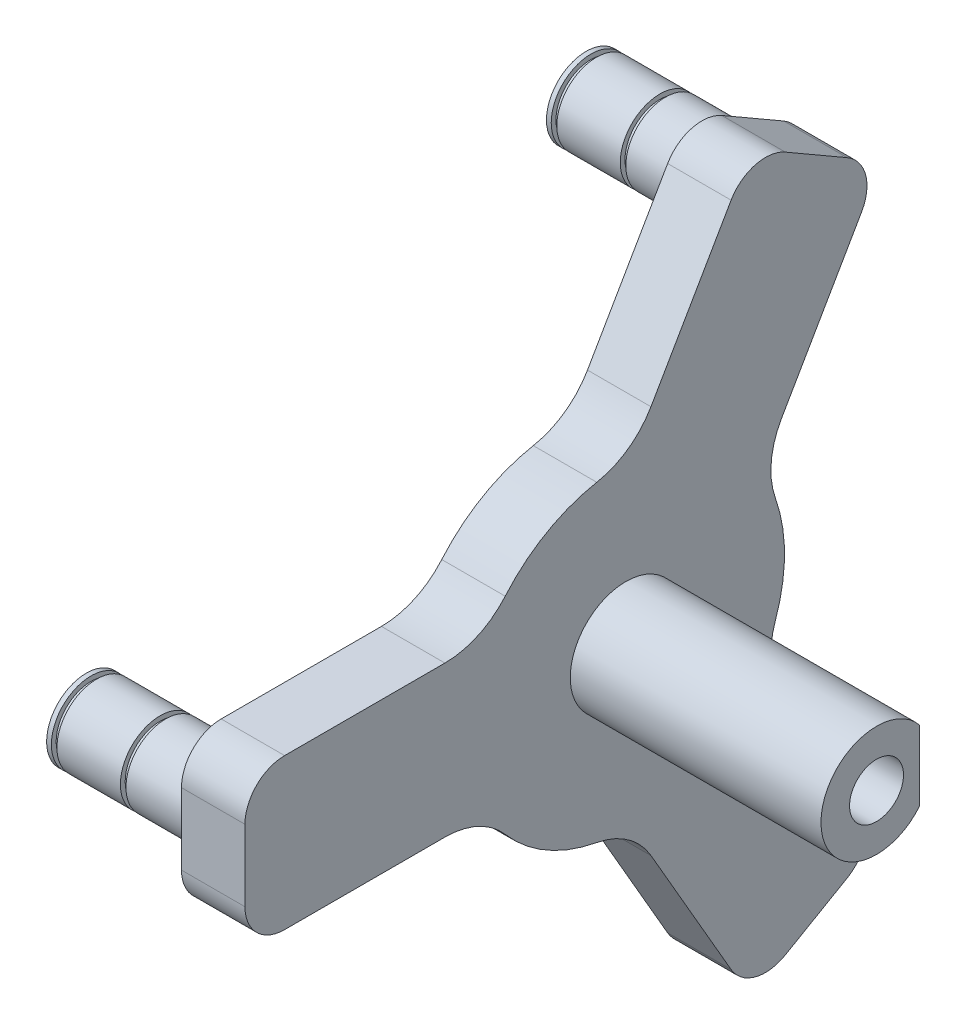
SolidWorks part; units mm, degrees
ref_plane "Front Plane" through (0, 0, 0) normal (1, 0, 0) x (0, 1, 0)
ref_plane "Top Plane" through (0, 0, 0) normal (0, 0, 1) x (0, 1, 0)
ref_plane "Right Plane" through (0, 0, 0) normal (0, 1, 0) x (-1, 0, 0)
sketch "Sketch1" plane through (0, 0, 0) normal (1, 0, 0) x (0, 1, 0)
  line L0 (0, 0) -> (0, 48) construction
  line L1 (46.3192, -15.7728) -> (19.9918, -0.5726) construction
  line L2 (36.8192, -32.2272) -> (10.4918, -17.0271) construction
  line L3 (-9.5, 48) -> (9.5, 48) construction
  line L4 (9.5, 48) -> (9.5, 17.5997) construction
  line L5 (-9.5, 48) -> (-9.5, 17.5997) construction
  line L6 (46.3192, -15.7728) -> (36.8192, -32.2272) construction
  line L7 (-36.8192, -32.2272) -> (-10.4918, -17.0271) construction
  line L8 (-46.3192, -15.7728) -> (-19.9918, -0.5726) construction
  line L9 (-36.8192, -32.2272) -> (-46.3192, -15.7728) construction
  line L10 (-19.9918, -0.5726) -> (-46.3192, -15.7728)
  line L11 (-46.3192, -15.7728) -> (-36.8192, -32.2272)
  line L12 (-36.8192, -32.2272) -> (-10.4918, -17.0271)
  line L13 (10.4918, -17.0271) -> (36.8192, -32.2272)
  line L14 (36.8192, -32.2272) -> (46.3192, -15.7728)
  line L15 (46.3192, -15.7728) -> (19.9918, -0.5726)
  line L16 (9.5, 17.5997) -> (9.5, 48)
  line L17 (9.5, 48) -> (-9.5, 48)
  line L18 (-9.5, 48) -> (-9.5, 17.5997)
  arc A0 (-9.5, 17.5997) -> (-19.9918, -0.5726) centre (0, 0) ccw construction
  arc A1 (19.9918, -0.5726) -> (9.5, 17.5997) centre (0, 0) ccw construction
  arc A2 (-10.4918, -17.0271) -> (10.4918, -17.0271) centre (0, 0) ccw construction
  arc A3 (-10.4918, -17.0271) -> (10.4918, -17.0271) centre (0, 0) ccw
  arc A4 (-10.4918, -17.0271) -> (10.4918, -17.0271) centre (0, 0) ccw construction
  arc A5 (-10.4918, -17.0271) -> (10.4918, -17.0271) centre (0, 0) ccw construction
  arc A6 (19.9918, -0.5726) -> (9.5, 17.5997) centre (0, 0) ccw construction
  arc A7 (19.9918, -0.5726) -> (9.5, 17.5997) centre (0, 0) ccw
  arc A8 (19.9918, -0.5726) -> (9.5, 17.5997) centre (0, 0) ccw construction
  arc A9 (-9.5, 17.5997) -> (-19.9918, -0.5726) centre (0, 0) ccw construction
  arc A10 (-9.5, 17.5997) -> (-19.9918, -0.5726) centre (0, 0) ccw construction
  arc A11 (-9.5, 17.5997) -> (-19.9918, -0.5726) centre (0, 0) ccw
  point P18 (0, 0)
  dimension "D4" = 40
  dimension "D1" = 19
  dimension "D2" = 3
  dimension "D3" = 48
extrude "Boss-Extrude2" add sketch "Sketch1" along normal blind 8
fillet "Fillet1" radius 10 6 edges at (4, 10.4918, -17.0271) (4, -10.4918, -17.0271) (4, -19.9918, -0.5726) (4, -9.5, 17.5997) (4, 19.9918, -0.5726) (4, 9.5, 17.5997)
fillet "Fillet3" radius 5 2 edges at (4, 9.5, 48) (4, -9.5, 48)
fillet "Fillet4" radius 5 4 edges at (4, 46.3192, -15.7728) (4, 36.8192, -32.2272) (4, -36.8192, -32.2272) (4, -46.3192, -15.7728)
sketch "Sketch2" plane through (0, 0, 0) normal (-1, 0, 0) x (0, -1, 0)
  line L0 (0, 0) -> (0, 42) construction
  line L1 (0, 0) -> (-36.3731, -21) construction
  line L2 (0, 0) -> (36.3731, -21) construction
  circle A0 centre (0, 42) radius 5
  circle A1 centre (-36.3731, -21) radius 5
  circle A2 centre (36.3731, -21) radius 5
  dimension "D1" = 10
  dimension "D2" = 42
sketch "Sketch3" plane through (0, 0, 0) normal (-1, 0, 0) x (0, -1, 0)
  circle A0 centre (0, 0) radius 5
  dimension "D1" = 10
extrude "Boss-Extrude3" add sketch "Sketch3" along normal blind 10
extrude "Boss-Extrude4" add sketch "Sketch2" along normal blind 18
sketch "Sketch4" plane through (8, 0, 0) normal (1, 0, 0) x (0, 1, 0)
  circle A0 centre (0, 0) radius 7
  dimension "12" = 14
extrude "Boss-Extrude5" add sketch "Sketch4" along normal blind 31.6
sketch "Sketch5" plane through (39.6, 0, 0) normal (1, 0, 0) x (0, 1, 0)
  line L0 (-4.45, -5.4035) -> (4.45, -5.4035)
  circle A0 centre (0, 0) radius 7 construction
  circle A1 centre (0, 0) radius 7 construction
  arc A2 (-4.45, -5.4035) -> (4.45, -5.4035) centre (0, 0) ccw
  dimension "D1" = 8.9
extrude "Cut-Extrude1" cut sketch "Sketch5" against normal blind 8
sketch "Sketch7" plane through (0, 0, 0) normal (0, 1, 0) x (-1, 0, 0)
  line L0 (18, 47) -> (0, 47) construction
  line L6 (8.7, 46.4) -> (8, 46.4)
  line L12 (8.7, 46.4) -> (8.7, 47.6)
  line L13 (8.7, 47.6) -> (8, 47.6)
  line L14 (21.8155, 42) -> (-10.848, 42) construction
  line L15 (8, 46.4) -> (8, 47.6)
  line L16 (8.7, 46.4) -> (8, 47.6) construction
  line L17 (8.7, 47.6) -> (8, 46.4) construction
  line L18 (17.4, 46.4) -> (16.7, 46.4)
  line L19 (17.4, 46.4) -> (17.4, 47.6)
  line L20 (17.4, 47.6) -> (16.7, 47.6)
  line L21 (16.7, 46.4) -> (16.7, 47.6)
  line L22 (17.4, 46.4) -> (16.7, 47.6) construction
  line L23 (17.4, 47.6) -> (16.7, 46.4) construction
  line L25 (0, 37) -> (0, 47) construction
  point P0 (8.35, 47)
  point P7 (17.05, 47)
  dimension "D1" = 0.7
  dimension "D2" = 0.6
  dimension "D3" = 8
  dimension "D4" = 5
  dimension "D5" = 8
revolve "Cut-Revolve1" cut sketch "Sketch7" angle 360 about L14
pattern_circular "CirPattern1" count 3 every 120 about axis through (0, 0, 0) along (1, 0, 0) of "Cut-Revolve1"
sketch "Sketch8" plane through (39.6, 0, 0) normal (1, 0, 0) x (0, 1, 0)
  circle A0 centre (0, 0) radius 3.4
  dimension "D1" = 6.8
extrude "Cut-Extrude2" cut sketch "Sketch8" against normal blind 14
